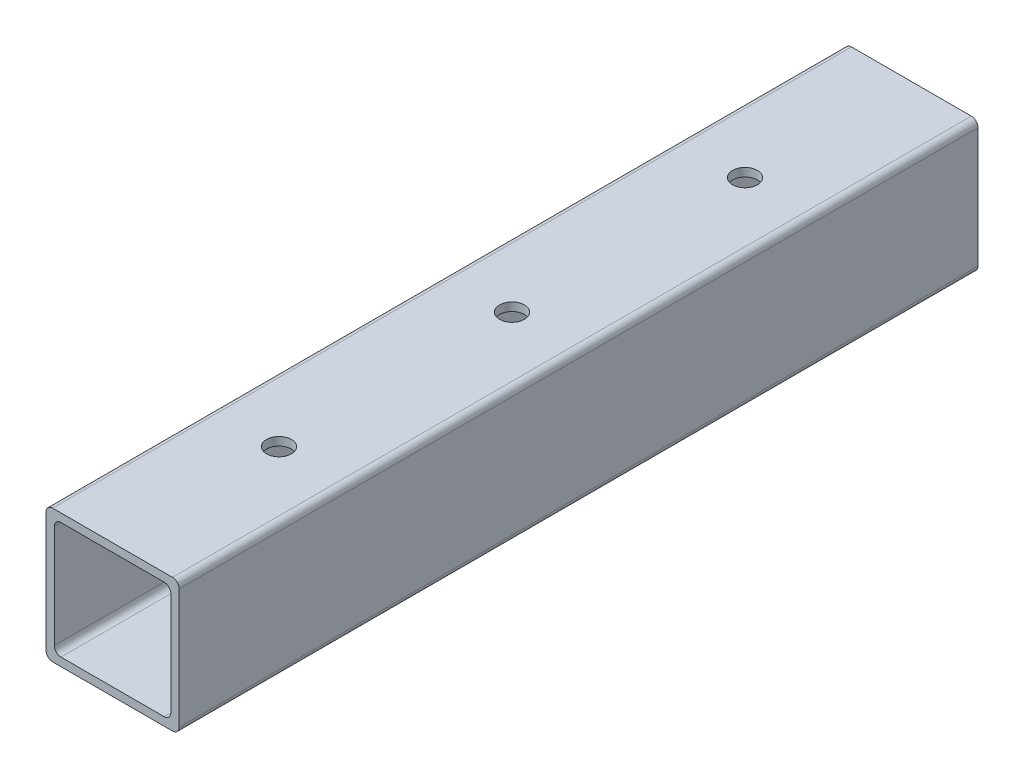
SolidWorks part; units mm, degrees
ref_plane "Front Plane" through (0, 0, 0) normal (0, 0, 1) x (1, 0, 0)
ref_plane "Top Plane" through (0, 0, 0) normal (0, 1, 0) x (1, 0, 0)
ref_plane "Right Plane" through (0, 0, 0) normal (1, 0, 0) x (0, 0, -1)
sketch "Sketch1" plane through (0, 0, 0) normal (0, 0, 1) x (1, 0, 0)
  line L0 (-157.2451, 0) -> (157.2451, 0) construction
  line L1 (0, -105.8578) -> (0, 105.8578) construction
  line L2 (-19.685, 22.225) -> (19.685, 22.225)
  line L3 (-22.86, -25.4) -> (22.86, -25.4)
  line L4 (-25.4, -22.86) -> (-25.4, 22.86)
  line L5 (-22.86, 25.4) -> (22.86, 25.4)
  line L6 (25.4, -22.86) -> (25.4, 22.86)
  line L7 (-25.4, -25.4) -> (25.4, 25.4) construction
  line L8 (-25.4, 25.4) -> (25.4, -25.4) construction
  line L9 (22.225, -19.685) -> (22.225, 19.685)
  line L10 (-19.685, -22.225) -> (19.685, -22.225)
  line L11 (-22.225, -19.685) -> (-22.225, 19.685)
  line L12 (-25.4, -25.4) -> (25.4, -25.4) construction
  line L13 (-25.4, -25.4) -> (-25.4, 25.4) construction
  line L14 (-22.225, -22.225) -> (22.225, -22.225) construction
  line L15 (-22.225, -22.225) -> (-22.225, 22.225) construction
  line L16 (22.225, -22.225) -> (22.225, 22.225) construction
  line L17 (25.4, -25.4) -> (25.4, 25.4) construction
  line L18 (-22.225, 22.225) -> (22.225, 22.225) construction
  line L19 (-25.4, 25.4) -> (25.4, 25.4) construction
  arc A0 (-22.86, -25.4) -> (-25.4, -22.86) centre (-22.86, -22.86) cw
  arc A1 (-19.685, -22.225) -> (-22.225, -19.685) centre (-19.685, -19.685) cw
  arc A2 (22.225, -19.685) -> (19.685, -22.225) centre (19.685, -19.685) cw
  arc A3 (22.86, -25.4) -> (25.4, -22.86) centre (22.86, -22.86) ccw
  arc A4 (19.685, 22.225) -> (22.225, 19.685) centre (19.685, 19.685) cw
  arc A5 (22.86, 25.4) -> (25.4, 22.86) centre (22.86, 22.86) cw
  arc A6 (-19.685, 22.225) -> (-22.225, 19.685) centre (-19.685, 19.685) ccw
  arc A7 (-25.4, 22.86) -> (-22.86, 25.4) centre (-22.86, 22.86) cw
  point P0 (0, 0)
  point P4 (0, 0)
  point P8 (0, 0)
  dimension "D4" = 2.54
  dimension "D1" = 50.8
  dimension "D2" = 50.8
  dimension "D3" = 3.175
extrude "Boss-Extrude1" add sketch "Sketch1" along normal mid plane 304.8
sketch "Sketch2" plane through (0, 0, 0) normal (0, 1, 0) x (1, 0, 0)
  line L0 (-216.6558, 0) -> (216.6558, 0) construction
  line L1 (0, 191.3651) -> (0, -191.3651) construction
  circle A0 centre (0, 0) radius 4.7625
  circle A1 centre (0, 88.9) radius 4.7625
  circle A2 centre (0, -88.9) radius 4.7625
  point P4 (0, 0)
  point P8 (0, 0)
  dimension "D1" = 9.525
  dimension "D2" = 2
extrude "Cut-Extrude1" cut sketch "Sketch2" against normal mid plane 152.4
